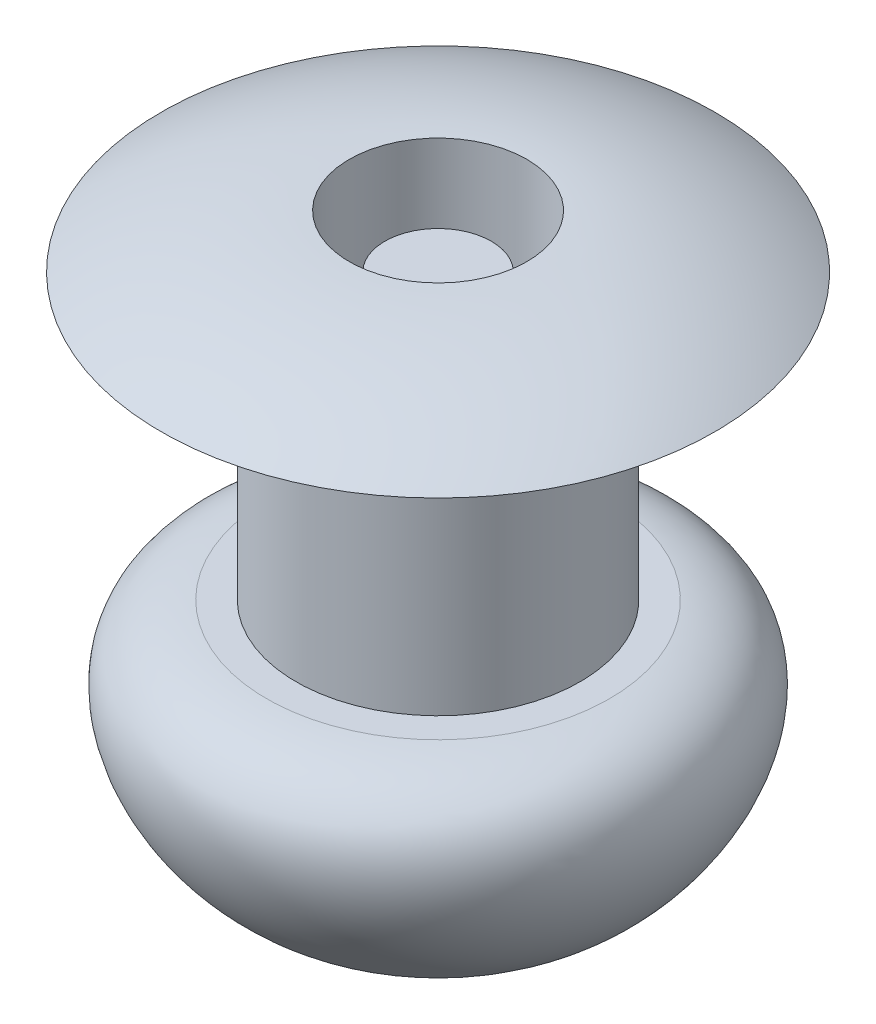
SolidWorks part; units mm, degrees
material "AISI 316 Stal nierdzewna odprężona (SS)"
ref_plane "Płaszczyzna przednia" through (0, 0, 0) normal (0, 0, 1) x (1, 0, 0)
ref_plane "Płaszczyzna górna" through (0, 0, 0) normal (0, 1, 0) x (1, 0, 0)
ref_plane "Płaszczyzna prawa" through (0, 0, 0) normal (1, 0, 0) x (0, 0, -1)
sketch "Szkic1" plane through (0, 0, 0) normal (1, 0, 0) x (0, 0, -1)
  line L0 (0, 0) -> (0, -4)
  line L1 (0, 0) -> (-0.75, 0)
  line L2 (-0.75, 0) -> (-0.75, -4)
  line L3 (-0.75, -4) -> (-1.25, -4)
  line L4 (-1.25, -4) -> (-1.25, 0.75)
  line L5 (-3.9, 0) -> (-2, 0)
  line L6 (-2, 0) -> (-2, -4)
  line L7 (-2, -4) -> (-2.4139, -4)
  line L8 (0, 0) -> (0, 0.4842) construction
  line L10 (0, -4) -> (0, -5.5)
  line L11 (-573, -4) -> (7, -4) construction
  arc A0 (-1.25, 0.75) -> (-3.9, 0) centre (-1.25, -4.3067) ccw
  ellipse E0 centre (0, -4.75) end of major axis (-1.75, -4.75) minor radius 0.75 (-0.956, -5.3782) -> (0, -5.5) ccw
  spline S0 degree 3 poles (-2.4139, -4) (-3.8586, -4.1633) (-3.5584, -6.323) (-0.9713, -7.8719) (-0.3411, -5.792) (-0.956, -5.3782) knots 0 0 0 0 0.454219 0.705201 1 1 1 1
  point P1 (0, 0)
  point P25 (-2.2069, -4)
  dimension "D1" = 7.8
  dimension "D2" = 2.5
  dimension "D3" = 4
  dimension "D4" = 0.75
  dimension "D5" = 1.5
  dimension "D6" = 1.5
  dimension "D7" = 3.5
  dimension "D8" = 3.1855
  dimension "D9" = 2.5026
  dimension "D10" = 1.9
  dimension "D11" = 1.3782
  dimension "D12" = 0.5792
  dimension "D13" = 4.8278
  dimension "D14" = 3.3858
  dimension "D15" = 2.8395
  dimension "D16" = 1.25
  dimension "D17" = 0.6409
  dimension "D18" = 0.956
revolve "Obrót1" add sketch "Szkic1" angle 360 about L8
